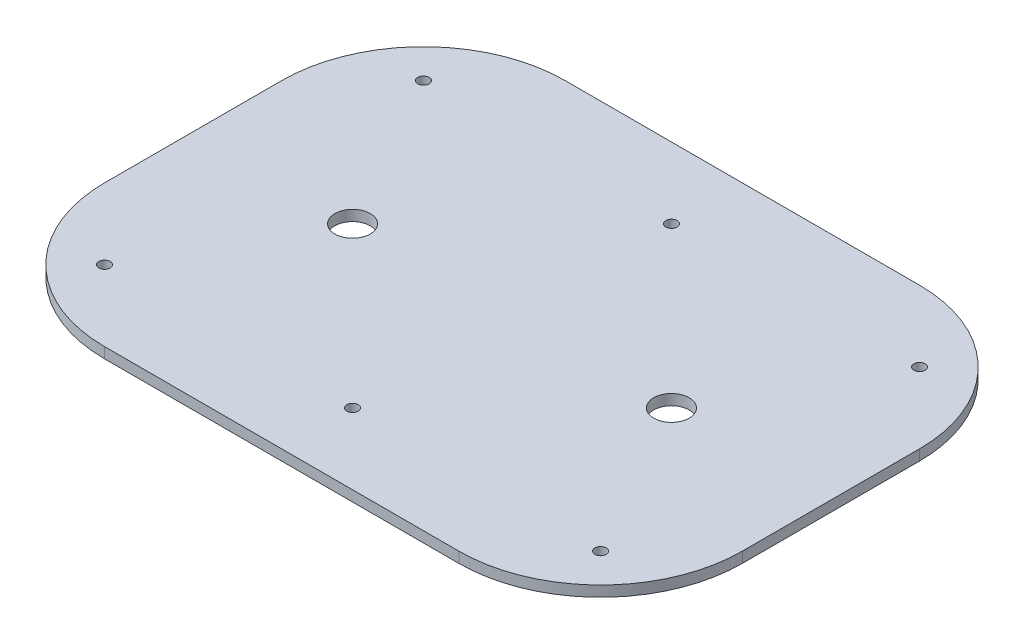
SolidWorks part; units mm, degrees
ref_plane "Front Plane" through (0, 0, 0) normal (0, 0, 1) x (1, 0, 0)
ref_plane "Top Plane" through (0, 0, 0) normal (0, 1, 0) x (1, 0, 0)
ref_plane "Right Plane" through (0, 0, 0) normal (1, 0, 0) x (0, 0, -1)
sketch "Sketch1" plane through (0, 0, 0) normal (0, 1, 0) x (1, 0, 0)
  line L1 (-90, 65) -> (90, 65)
  line L2 (-90, 65) -> (-90, -65)
  line L3 (-90, -65) -> (90, -65)
  line L4 (90, 65) -> (90, -65)
  line L5 (-90, 65) -> (90, -65) construction
  line L6 (-90, -65) -> (90, 65) construction
  point P0 (0, 0)
  dimension "D1" = 180
  dimension "D2" = 130
extrude "Boss-Extrude1" add sketch "Sketch1" along normal blind 3
fillet "Fillet1" radius 40 2 edges at (-90, 1.5, 65) (-90, 1.5, -65)
fillet "Fillet2" radius 40 2 edges at (90, 1.5, -65) (90, 1.5, 65)
sketch "Sketch3" plane through (0, 3, 0) normal (0, 1, 0) x (1, 0, 0)
  line L0 (-90, -65) -> (-90, 65) construction
  line L1 (-90, -65) -> (90, -65) construction
  point P5 (-45, 0)
  point P7 (45, 0)
  dimension "D1" = 130
  dimension "D2" = 45
  dimension "D3" = 135
  dimension "D4" = 65
  dimension "D5" = 65
hole_wizard "Ø10.0 (10) Diameter Hole1" positions "Sketch3" profile "Sketch4" hole size "Ø10.0" standard "ANSI Metric" end condition through all
sketch "Sketch4" plane through (45, 3, 0) normal (1, 0, 0) x (0, 0, 1)
  line L0 (0, 0) -> (0, 3)
  line L1 (0, 3) -> (5, 3)
  line L2 (5, 3) -> (5, 0)
  line L5 (5, 0) -> (0, 0)
  line L11 (0, -6.35) -> (0, 107.95) construction
  dimension "Thru Hole Dia." = 10
  dimension "Thru Hole Depth" = 3
hole_wizard "Ø3.2 (3.2) Diameter Hole1" positions "3DSketch1" profile "Sketch5" hole size "Ø3.2" standard "ANSI Metric" end condition through all
sketch3d "3DSketch1"
  line L0 (-90, 3, -25) -> (-90, 3, 25) construction
  line L1 (-50, 3, 65) -> (50, 3, 65) construction
  line L2 (50, 3, -65) -> (-50, 3, -65) construction
  line L3 (90, 3, 25) -> (90, 3, -25) construction
  point P0 (-70, 3, -45)
  point P2 (0, 3, -45)
  point P4 (70, 3, -45)
  point P6 (-70, 3, 45)
  point P8 (0, 3, 45)
  point P10 (70, 3, 45)
  dimension "D1" = 20
  dimension "D2" = 20
  dimension "D3" = 20
  dimension "D4" = 160
  dimension "D5" = 20
  dimension "D6" = 20
  dimension "D7" = 90
  dimension "D8" = 20
  dimension "D9" = 20
  dimension "D10" = 90
  dimension "D11" = 20
  dimension "D12" = 20
sketch "Sketch5" plane through (-70, 3, -45) normal (1, 0, 0) x (0, 0, 1)
  line L0 (0, 0) -> (0, 3)
  line L1 (0, 3) -> (1.6, 3)
  line L2 (1.6, 3) -> (1.6, 0)
  line L5 (1.6, 0) -> (0, 0)
  line L11 (0, -6.35) -> (0, 107.95) construction
  dimension "Thru Hole Dia." = 3.2
  dimension "Thru Hole Depth" = 3
